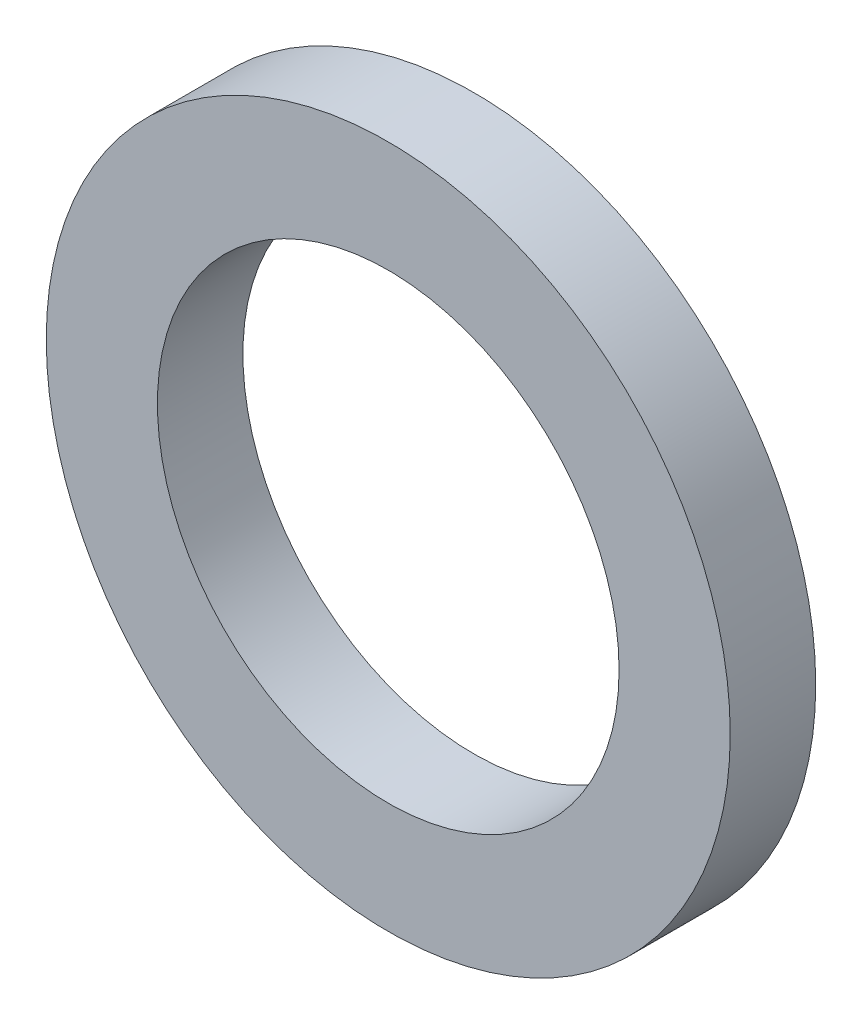
SolidWorks part; units mm, degrees
ref_plane "前视基准面" through (0, 0, 0) normal (0, 0, 1) x (1, 0, 0)
ref_plane "上视基准面" through (0, 0, 0) normal (0, 1, 0) x (1, 0, 0)
ref_plane "右视基准面" through (0, 0, 0) normal (1, 0, 0) x (0, 0, -1)
other "Configuration Table"
sketch "Profile_1" plane through (0, 0, 0) normal (0, 0, 1) x (1, 0, 0)
  circle A0 centre (0, 0) radius 6
  circle A1 centre (0, 0) radius 4.05
extrude "Ring" add sketch "Profile_1" along normal blind 1.5 from offset 0
